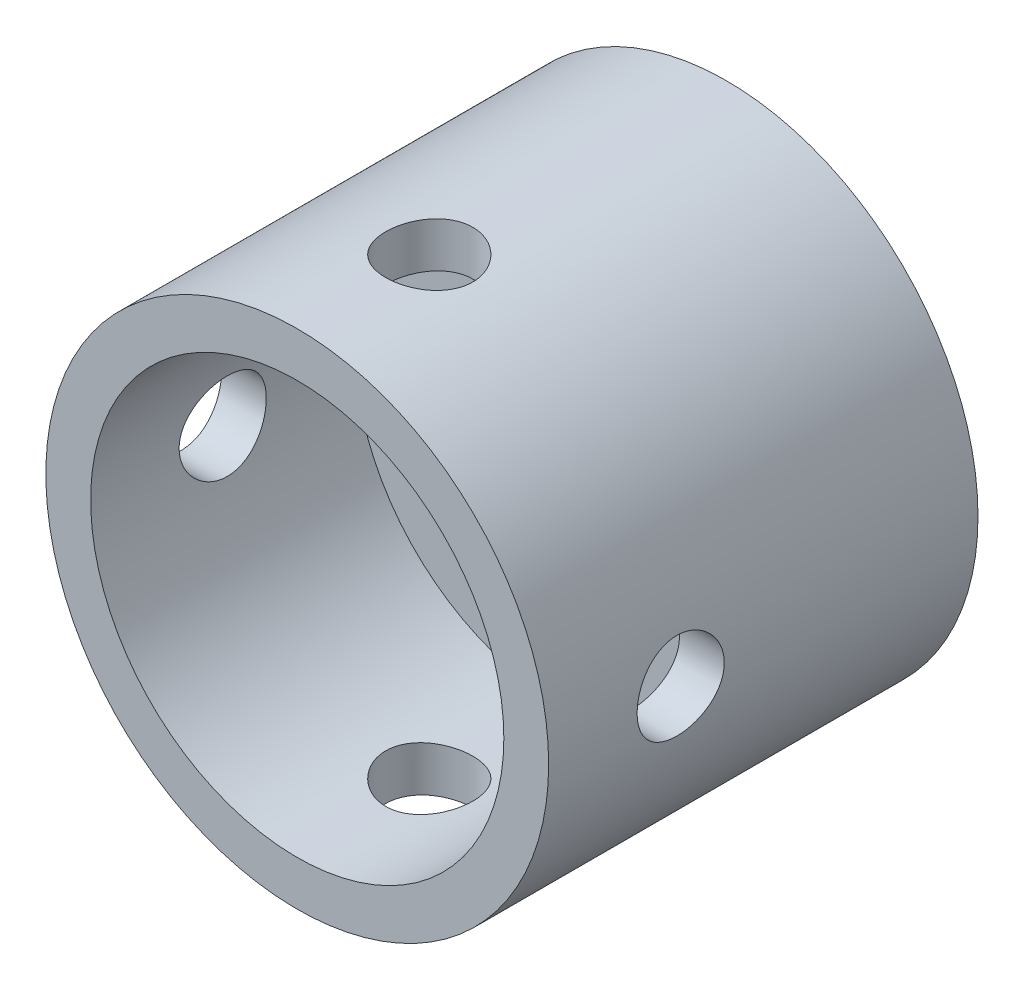
SolidWorks part; units mm, degrees
material "6061-T6 (SS)"
ref_plane "Front Plane" through (0, 0, 0) normal (0, 0, 1) x (1, 0, 0)
ref_plane "Top Plane" through (0, 0, 0) normal (0, 1, 0) x (1, 0, 0)
ref_plane "Right Plane" through (0, 0, 0) normal (1, 0, 0) x (0, 0, -1)
sketch "Sketch1" plane through (0, 0, 0) normal (1, 0, 0) x (0, 0, -1)
  line L0 (0, 0) -> (0, 2.7375) construction
  line L1 (0, 6.35) -> (3.175, 6.35)
  line L2 (3.175, 6.35) -> (3.175, 5.5315)
  line L3 (5.7937, 8.5) -> (5.7937, 13) construction
  line L4 (5.7937, 13) -> (0.7938, 13) construction
  line L5 (0.7938, 13) -> (0.7938, 8.5) construction
  line L6 (5.7937, 13) -> (5.7937, 14) construction
  line L7 (5.7937, 14) -> (6.7937, 14) construction
  line L8 (6.7937, 14) -> (6.7937, 7.5) construction
  line L9 (0, 8.5) -> (5.7937, 8.5)
  line L10 (0, 8.5) -> (0, 6.35) construction
  line L11 (5.7937, 8.5) -> (5.7937, 7.5)
  line L12 (5.7937, 7.5) -> (39.6687, 7.5)
  line L13 (6.7937, 14) -> (6.7937, 20.32) construction
  line L14 (6.7937, 20.32) -> (16.3187, 20.32) construction
  line L15 (16.3187, 20.32) -> (16.3187, 7.5) construction
  line L16 (11.5562, 19.5) -> (11.5562, 7.5) construction
  line L17 (11.5562, 19.5) -> (16.5562, 19.5) construction
  line L18 (16.5562, 19.5) -> (16.5562, 7.5) construction
  line L19 (9.175, 20.32) -> (9.175, 0) construction
  line L20 (16.5562, 19.5) -> (16.5562, 14) construction
  line L21 (16.5562, 14) -> (17.5562, 14) construction
  line L22 (17.5562, 14) -> (17.5562, 7.5) construction
  line L23 (0, 0) -> (31.9294, 0)
  line L24 (17.5562, 14) -> (17.5562, 26.67) construction
  line L25 (17.5562, 26.67) -> (27.0812, 26.67) construction
  line L26 (27.0812, 26.67) -> (27.0812, 7.5) construction
  line L27 (22.3187, 7.5) -> (22.3187, 19.5) construction
  line L28 (22.3187, 19.5) -> (27.3187, 19.5) construction
  line L29 (27.3187, 19.5) -> (27.3187, 7.5) construction
  line L30 (19.9375, 26.67) -> (19.9375, 0) construction
  line L31 (27.3187, 19.5) -> (27.3187, 14) construction
  line L32 (27.3187, 14) -> (28.3187, 14) construction
  line L33 (28.3187, 14) -> (28.3187, 7.5) construction
  line L34 (28.3187, 19.5) -> (33.3187, 19.5) construction
  line L35 (33.3187, 19.5) -> (33.3187, 7.5) construction
  line L36 (33.3187, 2.3813) -> (33.3187, 38.6538) construction
  line L37 (26.9687, 0) -> (26.9687, 30.1625) construction
  line L38 (28.5562, 30.1625) -> (28.5562, 0) construction
  line L39 (0, 0) -> (0, 2.7375) construction
  line L40 (6.35, 42.8625) -> (6.35, 0) construction
  line L41 (4.7625, 50.8) -> (4.7625, 0) construction
  line L42 (-17.4625, 46.0375) -> (-17.4625, 53.5375)
  line L43 (3.175, 5.5315) -> (23.1125, 5.5315)
  line L44 (0, 4.7378) -> (13.0644, 4.7378) construction
  line L45 (0, 2.7375) -> (14.0479, 2.7375)
  line L46 (11.9076, 4.7378) -> (9.9073, 2.7375) construction
  line L47 (17.2049, 4.7378) -> (19.2052, 2.7375) construction
  line L48 (21.1281, 4.7378) -> (23.1284, 2.7375)
  line L49 (16.0481, 4.7378) -> (16.0481, 0) construction
  line L50 (7.9844, 4.7378) -> (5.9841, 2.7375) construction
  line L51 (13.0644, 4.7378) -> (15.0646, 2.7375) construction
  line L52 (16.0481, 4.7378) -> (14.0479, 2.7375)
  line L53 (29.1919, 2.7375) -> (31.9294, 0)
  line L54 (16.0481, 4.7378) -> (21.1281, 4.7378)
  line L55 (39.6687, 2.3813) -> (39.6687, 7.5)
  line L56 (0, 6.35) -> (0, 44.45) construction
  line L57 (23.1284, 2.7375) -> (29.1919, 2.7375)
  line L58 (23.1125, 5.5315) -> (24.5284, 3.175)
  line L59 (24.5284, 3.175) -> (29.8649, 3.175)
  line L60 (29.8649, 3.175) -> (30.3419, 2.3813)
  line L61 (30.3419, 2.3813) -> (39.6687, 2.3813)
  line L62 (30.3419, 2.3813) -> (29.5481, 2.3813)
  line L63 (0, 2.7375) -> (-3.175, 2.7375)
  line L64 (-3.175, 2.7375) -> (-3.175, 2)
  line L65 (-3.175, 2) -> (-9.9531, 2)
  line L66 (-9.9531, 2) -> (-9.9531, 0)
  line L67 (-9.9531, 0) -> (0, 0)
  line L68 (-3.175, 2.7375) -> (-3.175, 4.5)
  line L69 (-3.175, 4.5) -> (-7.175, 4.5)
  line L70 (-7.175, 4.5) -> (-7.175, 2)
  line L71 (-3.175, 3.5) -> (-1.5875, 3.5)
  line L72 (-1.5875, 3.5) -> (-1.5875, 8.5)
  line L73 (-1.5875, 8.5) -> (-16.1031, 8.5)
  line L74 (-14.5156, 3.429) -> (-14.5156, 3.81)
  line L75 (-14.5156, 3.81) -> (-7.175, 3.81)
  line L76 (-7.302, 0) -> (-7.302, 3.175)
  line L77 (-7.302, 3.175) -> (-8.8895, 3.175)
  line L78 (-8.8895, 3.175) -> (-8.8895, 0)
  line L79 (-10.35, 0) -> (-10.35, 3.429)
  line L80 (-10.35, 3.429) -> (-14.5156, 3.429)
  line L81 (-14.5156, 3.429) -> (-14.5156, 0)
  line L82 (-14.5156, 0) -> (-10.35, 0)
  line L83 (-7.175, 4.5) -> (-7.175, 6.985)
  line L84 (-7.175, 6.985) -> (-16.1031, 6.985)
  line L85 (-16.1031, 6.985) -> (-16.1031, 8.5)
  line L86 (-16.1031, 2.0828) -> (-16.1031, 6.985)
  line L87 (-14.5156, 2.0828) -> (-16.1031, 2.0828)
  circle A0 centre (-17.4625, 46.0375) radius 7.5
  circle A1 centre (-17.4625, 46.0375) radius 5.5315
  circle A2 centre (-17.4625, 53.1565) radius 2.3812
  circle A3 centre (-17.4625, 51.1562) radius 2.3812
  circle A4 centre (-17.4625, 46.0375) radius 12.7
  arc A5 (-14.9548, 53.1058) -> (-19.9702, 53.1058) centre (-17.4625, 53.1565) ccw
  circle A6 centre (-17.4625, 46.0375) radius 2.7375
  circle A7 centre (-17.4625, 46.0375) radius 4.7378
  circle A8 centre (-17.4625, 46.0375) radius 7.754
  circle A9 centre (9.175, 7.119) radius 2.3813 construction
  circle A10 centre (9.175, 5.3727) radius 2.3813 construction
  circle A11 centre (9.175, 5.1187) radius 2.3813 construction
  circle A12 centre (19.9375, 7.119) radius 2.3813 construction
  circle A13 centre (19.9375, 5.3727) radius 2.3813 construction
  circle A14 centre (19.9375, 5.1187) radius 2.3813 construction
  dimension "D24" = 15
  dimension "D25" = 4.7625
  dimension "D27" = 25.4
  dimension "D28" = 5.0165
  dimension "D29" = 0.7937
  dimension "D30" = 0.254
  dimension "D31" = 11.063
  dimension "D32" = 5.475
  dimension "D34" = 9.4755
  dimension "D37" = 4.7625
  dimension "D39" = 2.1273
  dimension "D1" = 8.5
  dimension "D2" = 3.175
  dimension "D3" = 6.35
  dimension "D4" = 5.7937
  dimension "D5" = 7.5
  dimension "D6" = 5
  dimension "D7" = 13
  dimension "D8" = 1
  dimension "D9" = 14
  dimension "D10" = 9.525
  dimension "D11" = 20.32
  dimension "D12" = 4.7625
  dimension "D13" = 5
  dimension "D14" = 2.3813
  dimension "D15" = 12
  dimension "D16" = 26.67
  dimension "D17" = 4.7625
  dimension "D18" = 2.3813
  dimension "D19" = 6.35
  dimension "D20" = 1.5875
  dimension "D21" = 6.35
  dimension "D22" = 1.5875
  dimension "D23" = 6.35
  dimension "D26" = 0.381
  dimension "D33" = 5.5315
  dimension "D35" = 4.7378
  dimension "D36" = 2.7375
  dimension "D38" = 0.381
  dimension "D40" = 45
  dimension "D41" = 5.2973
  dimension "D42" = 10.7625
  dimension "D43" = 1.1906
  dimension "D44" = 5.08
  dimension "D45" = 1.1906
  dimension "D46" = 8.0637
  dimension "D47" = 5.08
  dimension "D48" = 6.0635
  dimension "D49" = 45
  dimension "D50" = 6.0635
  dimension "D51" = 0.7937
  dimension "D52" = 59
  dimension "D53" = 3.175
  dimension "D54" = 0.7937
  dimension "D55" = 2.3813
  dimension "D56" = 2
  dimension "D57" = 4.5
  dimension "D58" = 4
  dimension "D59" = 1.5875
  dimension "D60" = 4.69
  dimension "D61" = 1.5875
  dimension "D62" = 4.1656
  dimension "D63" = 3.429
  dimension "D64" = 2.7781
  dimension "D65" = 1.5875
  dimension "D66" = 3.175
  dimension "D67" = 0.127
  dimension "D68" = 0.3969
  dimension "D69" = 1.5875
  dimension "D70" = 3.81
  dimension "D71" = 3.175
  dimension "D72" = 2.0828
  dimension "D73" = 14.5156
  dimension "D74" = 1
revolve "Revolve1" add sketch "Sketch1" angle 360 about L67
ref_plane "Plane1" through (0, 8.5, 0) normal (0, 1, 0) x (1, 0, 0)
sketch "Sketch2" plane through (0, 8.5, 0) normal (0, 1, 0) x (1, 0, 0)
  line L0 (-4.5, -7.175) -> (4.5, -7.175) construction
  line L1 (-4.5, -7.175) -> (4.5, -7.175)
  line L2 (-8.5, -16.1031) -> (8.5, -16.1031) construction
  line L3 (-8.5, -16.1031) -> (8.5, -16.1031)
  line L4 (0, -7.175) -> (0, -16.1031)
  point P6 (0, -11.6391)
hole_wizard "#4 Clearance Hole1" positions "Sketch4" profile "Sketch3" hole size "#4" standard "ANSI Inch"
sketch "Sketch4" plane through (0, 8.5, 0) normal (0, 1, 0) x (1, 0, 0)
  point P0 (0, -11.6391)
sketch "Sketch3" plane through (0, 8.5, 11.6391) normal (1, 0, 0) x (0, 0, 1)
  line L0 (0, 0) -> (0, 16.3702)
  line L1 (0, 16.3702) -> (1.4732, 15.485)
  line L2 (1.4732, 15.485) -> (1.4732, 0)
  line L5 (1.4732, 0) -> (0, 0)
  line L10 (0, 16.3702) -> (-1.4732, 15.485) construction
  line L11 (0, -6.35) -> (0, 107.95) construction
  dimension "Hole Dia." = 2.9464
  dimension "Hole Depth" = 15.485
  dimension "Drill Angle" = 118
pattern_circular "CirPattern1" count 4 over 360 about axis through (0, 0, 9.9531) along (0, 0, 1) of "#4 Clearance Hole1"
equation "\"D1@Sketch1\"=(17mm/2)"
equation "\"D5@Sketch1\"=15mm/2"
equation "\"D4@Sketch1\"=5mm+1/32"
equation "\"D6@Sketch1\"=5mm"
equation "\"D7@Sketch1\"=26mm/2"
equation "\"D8@Sketch1\"=1mm"
equation "\"D9@Sketch1\"=28mm/2"
equation "\"D11@Sketch1\"=(34-2)/20/2"
equation "\"D13@Sketch1\"=5mm"
equation "\"D15@Sketch1\"=24mm/2"
equation "\"D16@Sketch1\"=(44-2)/20/2"
equation "\"D33@Sketch1\"=\"D31@Sketch1\"/2"
equation "\"D35@Sketch1\"= \"D34@Sketch1\" / 2"
equation "\"D36@Sketch1\"= \"D32@Sketch1\" / 2"
equation "\"D39@Sketch1\" = \"D37@Sketch1\"/2-.01"
equation "\"D45@Sketch1\" = 3 / 64"
equation "\"D43@Sketch1\" = \"D45@Sketch1\""
equation "\"D47@Sketch1\"=\"D44@Sketch1\""
equation "\"D56@Sketch1\"=2mm"
equation "\"D57@Sketch1\"=9mm/2"
equation "\"D58@Sketch1\"=4mm"
equation "\"D63@Sketch1\"=.27/2"
equation "\"D64@Sketch1\"=1/16+3/64"
equation "\"D74@Sketch1\"=1mm"
